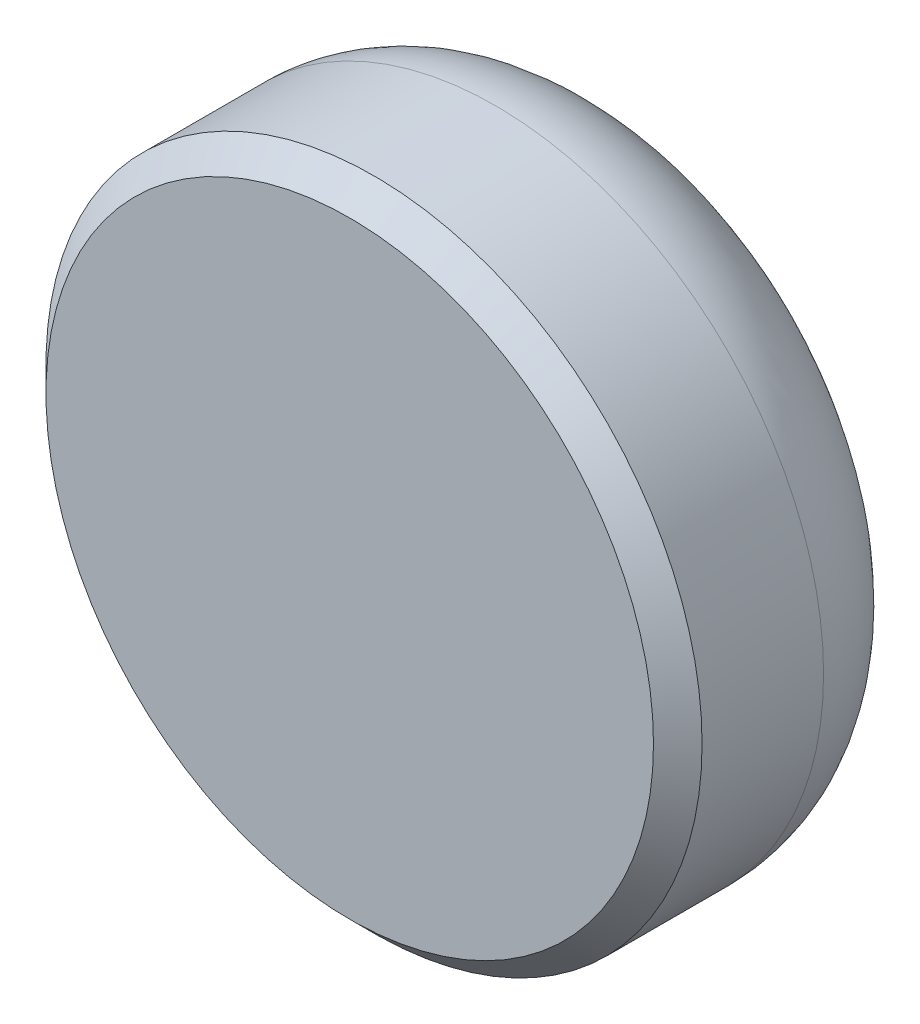
SolidWorks part; units mm, degrees
ref_plane "前视基准面" through (0, 0, 0) normal (0, 0, 1) x (1, 0, 0)
ref_plane "上视基准面" through (0, 0, 0) normal (0, 1, 0) x (1, 0, 0)
ref_plane "右视基准面" through (0, 0, 0) normal (1, 0, 0) x (0, 0, -1)
sketch "草图1" plane through (0, 0, 0) normal (0, 0, 1) x (1, 0, 0)
  circle A0 centre (0, 0) radius 2.7
  dimension "D1" = 5.4
extrude "凸台-拉伸1" add sketch "草图1" along normal blind 2.2
fillet "圆角1" radius 1 1 edges at (2.7, 0, 0)
chamfer "倒角1" distance 0.2 angle 45 1 edges at (2.7, 0, 2.2)
